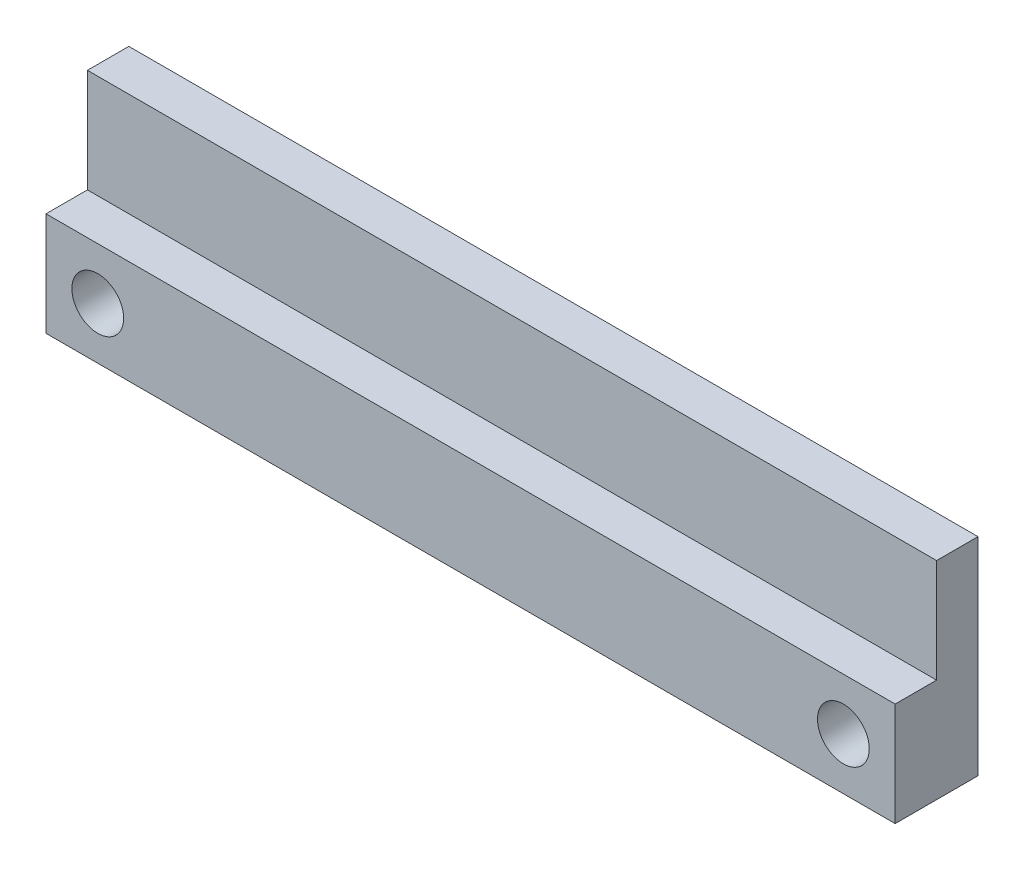
SolidWorks part; units mm, degrees
material "自訂玻璃纖維"
ref_plane "前基準面" through (0, 0, 0) normal (0, 0, 1) x (1, 0, 0)
ref_plane "上基準面" through (0, 0, 0) normal (0, 1, 0) x (1, 0, 0)
ref_plane "右基準面" through (0, 0, 0) normal (1, 0, 0) x (0, 0, -1)
sketch "草圖1" plane through (0, 0, 0) normal (0, 0, 1) x (1, 0, 0)
  line L1 (-15.8231, 10.9075) -> (25.1769, 10.9075)
  line L2 (-15.8231, 10.9075) -> (-15.8231, 0.9075)
  line L3 (-15.8231, 0.9075) -> (25.1769, 0.9075)
  line L4 (25.1769, 10.9075) -> (25.1769, 0.9075)
  dimension "D1" = 41
  dimension "D2" = 10
extrude "填料-伸長1" add sketch "草圖1" along normal blind 2
sketch "草圖2" plane through (0, 0, 2) normal (0, 0, 1) x (1, 0, 0)
  line L0 (25.1769, 0.9075) -> (25.1769, 10.9075) construction
  line L1 (-15.8231, 0.9075) -> (25.1769, 0.9075)
  line L2 (-15.8231, 0.9075) -> (-15.8231, 5.9075)
  line L3 (-15.8231, 5.9075) -> (25.1769, 5.9075)
  line L4 (25.1769, 0.9075) -> (25.1769, 5.9075)
  dimension "D1" = 5
extrude "填料-伸長2" add sketch "草圖2" along normal blind 2
sketch "草圖3" plane through (0, 0, 4) normal (0, 0, 1) x (1, 0, 0)
  line L0 (-15.8231, 0.9075) -> (25.1769, 0.9075) construction
  line L1 (-15.8231, 5.9075) -> (-15.8231, 0.9075) construction
  line L2 (25.1769, 0.9075) -> (25.1769, 5.9075) construction
  circle A0 centre (-13.3231, 3.4075) radius 1.25
  circle A1 centre (22.6769, 3.4075) radius 1.25
  point P8 (-15.8231, 3.4075)
  dimension "D1" = 2.5
  dimension "D2" = 2.5
  dimension "D3" = 2.5
  dimension "D4" = 2.5
  dimension "D5" = 2.5
extrude "除料-伸長1" cut sketch "草圖3" against normal through all
